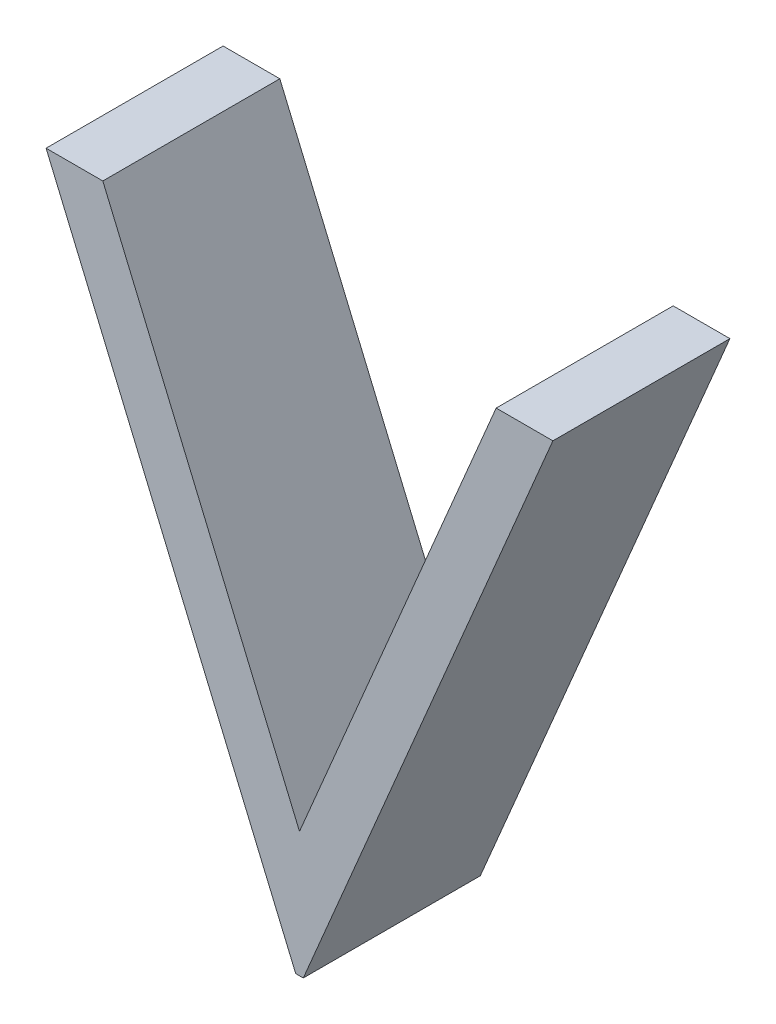
SolidWorks part; units mm, degrees
ref_plane "Plan de face" through (0, 0, 0) normal (0, 0, 1) x (1, 0, 0)
ref_plane "Plan de dessus" through (0, 0, 0) normal (0, 1, 0) x (1, 0, 0)
ref_plane "Plan de droite" through (0, 0, 0) normal (1, 0, 0) x (0, 0, -1)
sketch "Esquisse1" plane through (0, 0, 0) normal (0, 0, 1) x (1, 0, 0)
  text T0 "V" font "Century Gothic" height 5
extrude "Boss.-Extru.1" add sketch "Esquisse1" along normal blind 1.5
